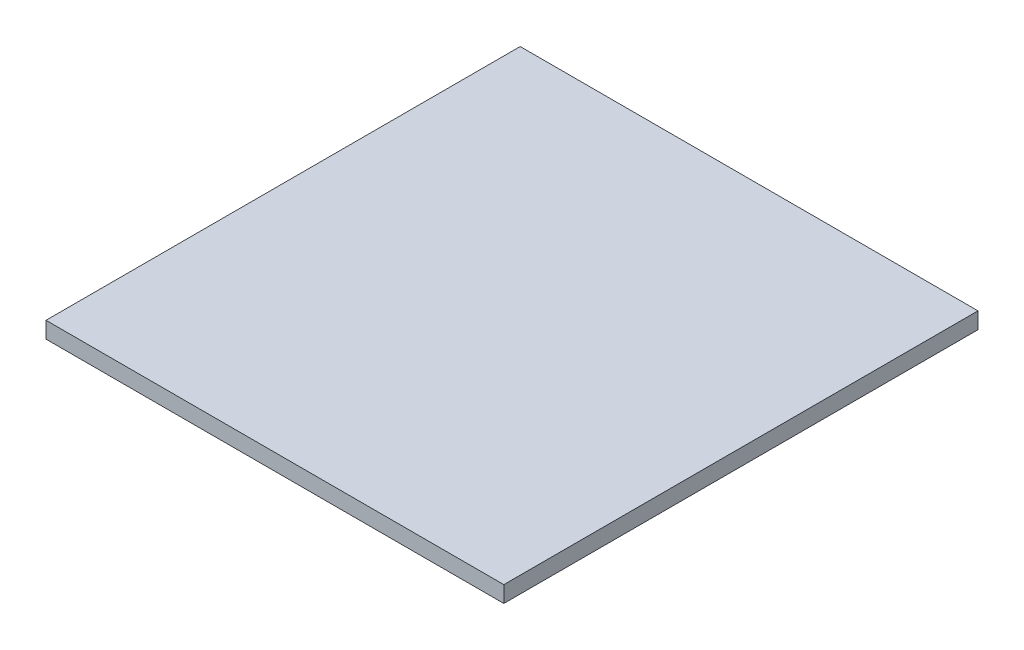
SolidWorks part; units mm, degrees
material "Acrylic (Medium-high impact)"
ref_plane "Front Plane" through (0, 0, 0) normal (0, 0, 1) x (1, 0, 0)
ref_plane "Top Plane" through (0, 0, 0) normal (0, 1, 0) x (1, 0, 0)
ref_plane "Right Plane" through (0, 0, 0) normal (1, 0, 0) x (0, 0, -1)
sketch "Sketch1" plane through (0, 0, 0) normal (0, 0, 1) x (1, 0, 0)
  line L1 (0, 0) -> (280, 0)
  line L2 (0, 0) -> (0, -10)
  line L3 (0, -10) -> (280, -10)
  line L4 (280, 0) -> (280, -10)
  dimension "D1" = 10
  dimension "D2" = 280
extrude "Boss-Extrude1" add sketch "Sketch1" along normal blind 290
